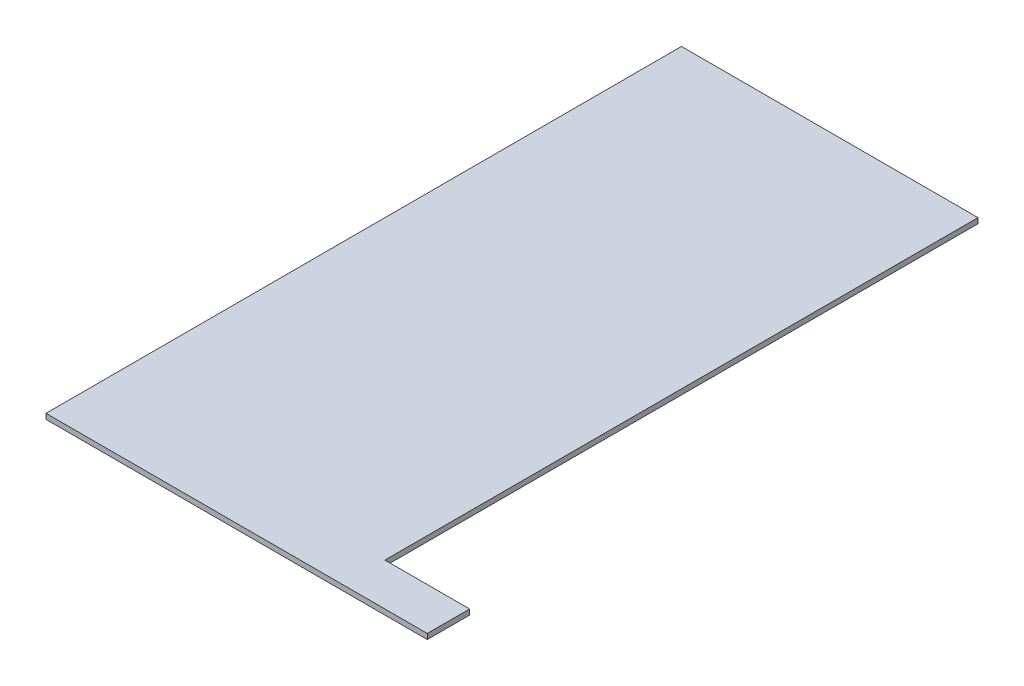
SolidWorks part; units mm, degrees
ref_plane "Front Plane" through (0, 0, 0) normal (0, 0, 1) x (1, 0, 0)
ref_plane "Top Plane" through (0, 0, 0) normal (0, 1, 0) x (1, 0, 0)
ref_plane "Right Plane" through (0, 0, 0) normal (1, 0, 0) x (0, 0, -1)
sketch "Sketch1" plane through (0, 0, 0) normal (0, 1, 0) x (1, 0, 0)
  line L0 (44.45, -95.25) -> (44.45, -82.55)
  line L1 (-44.45, 95.25) -> (44.45, 95.25)
  line L2 (-44.45, 95.25) -> (-44.45, -95.25)
  line L3 (-44.45, -95.25) -> (44.45, -95.25)
  line L4 (44.45, 95.25) -> (44.45, -95.25)
  line L5 (-44.45, 95.25) -> (44.45, -95.25) construction
  line L6 (-44.45, -95.25) -> (44.45, 95.25) construction
  line L7 (44.45, -95.25) -> (69.85, -95.25)
  line L8 (44.45, -82.55) -> (69.85, -82.55)
  line L9 (69.85, -95.25) -> (69.85, -82.55)
  point P0 (0, 0)
  dimension "D1" = 88.9
  dimension "D2" = 190.5
  dimension "D3" = 25.4
  dimension "D4" = 12.7
extrude "Boss-Extrude1" add sketch "Sketch1" along normal blind 1.5875 contours L4 L1 L2 L3 L0 | L7 L9 L8 L0
